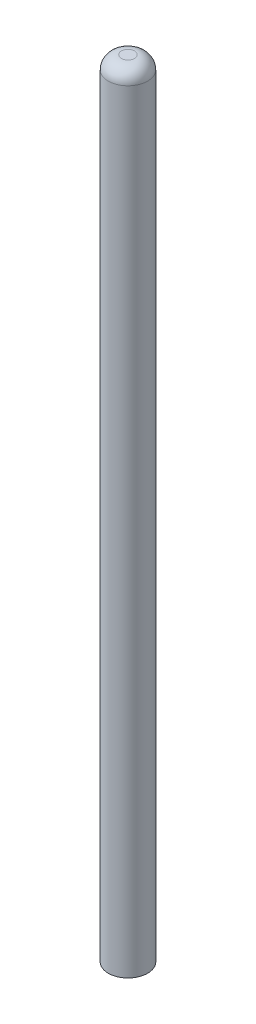
SolidWorks part; units mm, degrees
ref_plane "Front Plane" through (0, 0, 0) normal (0, 0, 1) x (1, 0, 0)
ref_plane "Top Plane" through (0, 0, 0) normal (0, 1, 0) x (1, 0, 0)
ref_plane "Right Plane" through (0, 0, 0) normal (1, 0, 0) x (0, 0, -1)
sketch "Sketch1" plane through (0, 0, 0) normal (0, 1, 0) x (1, 0, 0)
  circle A0 centre (0, 0) radius 1.5
  dimension "D1" = 3
extrude "Boss-Extrude1" add sketch "Sketch1" along normal blind 60
fillet "Fillet1" radius 1 1 edges at (0, 60, 1.5)
